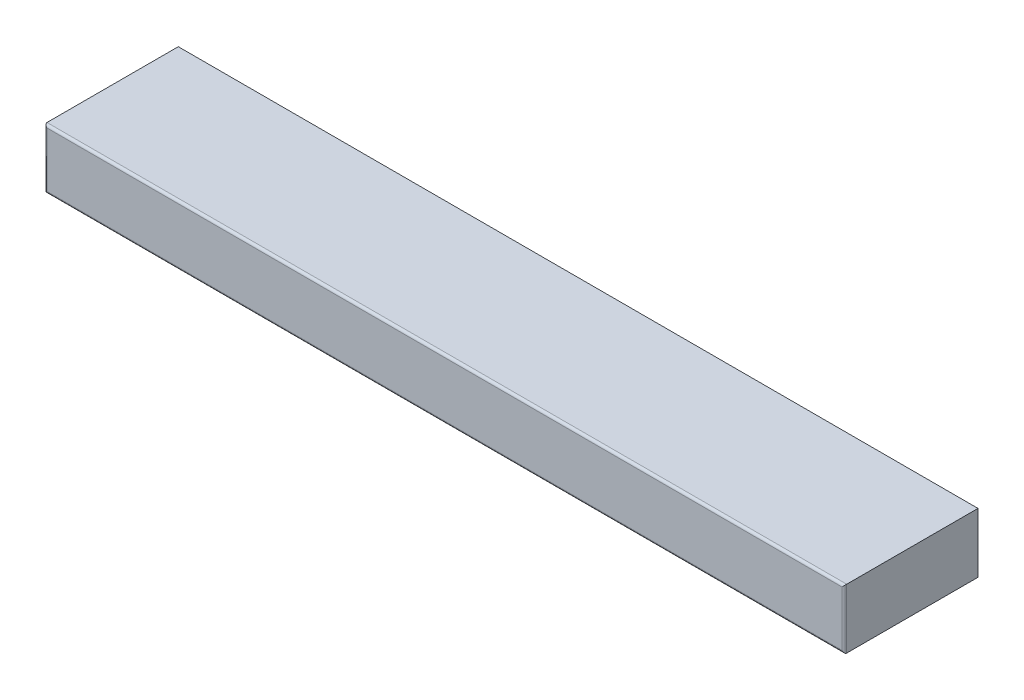
SolidWorks part; units mm, degrees
ref_plane "Front Plane" through (0, 0, 0) normal (0, 0, 1) x (1, 0, 0)
ref_plane "Top Plane" through (0, 0, 0) normal (0, 1, 0) x (1, 0, 0)
ref_plane "Right Plane" through (0, 0, 0) normal (1, 0, 0) x (0, 0, -1)
sketch "Sketch1" plane through (0, 0, 0) normal (0, 0, 1) x (1, 0, 0)
  line L1 (-33.5, -2.5) -> (33.5, -2.5)
  line L2 (-33.5, -2.5) -> (-33.5, 2.5)
  line L3 (-33.5, 2.5) -> (33.5, 2.5)
  line L4 (33.5, -2.5) -> (33.5, 2.5)
  line L5 (-33.5, -2.5) -> (33.5, 2.5) construction
  line L6 (-33.5, 2.5) -> (33.5, -2.5) construction
  point P0 (0, 0)
  dimension "D1" = 67
  dimension "D2" = 5
extrude "Boss-Extrude1" add sketch "Sketch1" along normal blind 11.2
fillet "Fillet1" radius 0.2 4 edges at (0, -2.5, 11.2) (-33.5, 0, 11.2) (0, 2.5, 11.2) (33.5, 0, 11.2)
